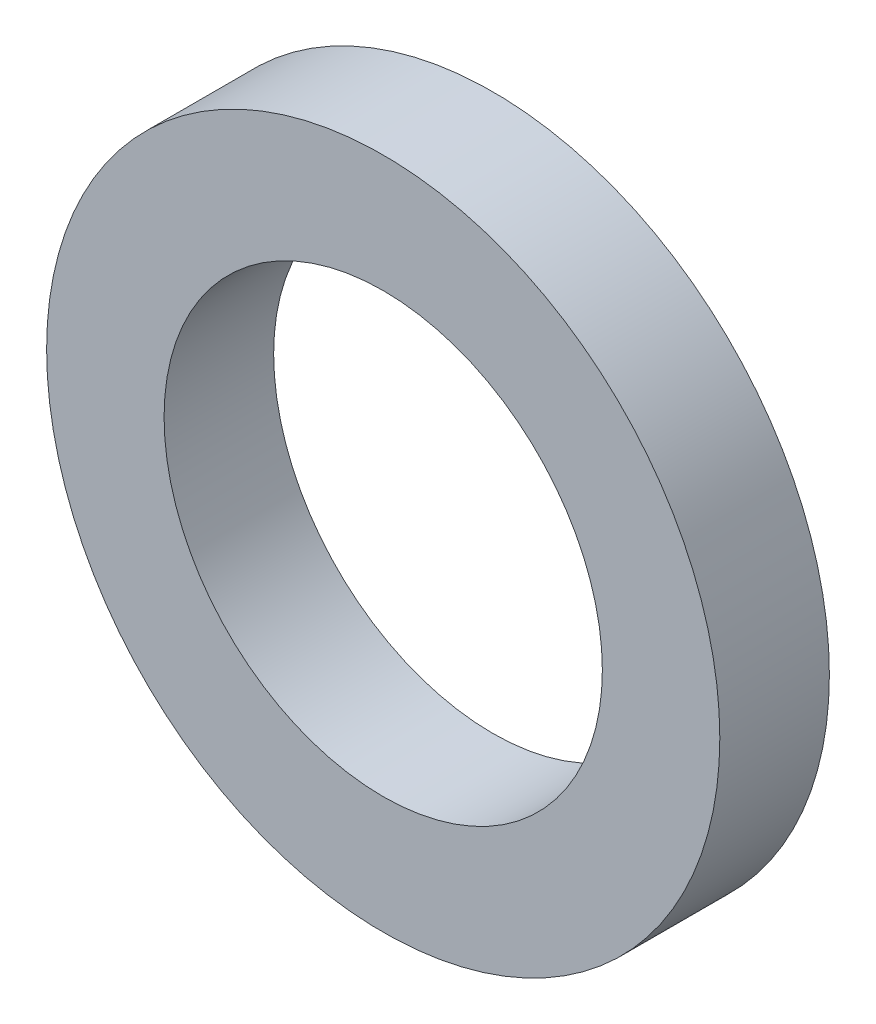
SolidWorks part; units mm, degrees
material "Birch Plywood"
ref_plane "Front Plane" through (0, 0, 0) normal (0, 0, 1) x (1, 0, 0)
ref_plane "Top Plane" through (0, 0, 0) normal (0, 1, 0) x (1, 0, 0)
ref_plane "Right Plane" through (0, 0, 0) normal (1, 0, 0) x (0, 0, -1)
sketch "Sketch1" plane through (0, 0, 0) normal (0, 0, 1) x (1, 0, 0)
  circle A0 centre (0, 0) radius 9.7536
  circle A1 centre (0, 0) radius 6.35
  dimension "D1" = 12.7
  dimension "D2" = 19.5072
extrude "Boss-Extrude1" add sketch "Sketch1" along normal blind 3.175
